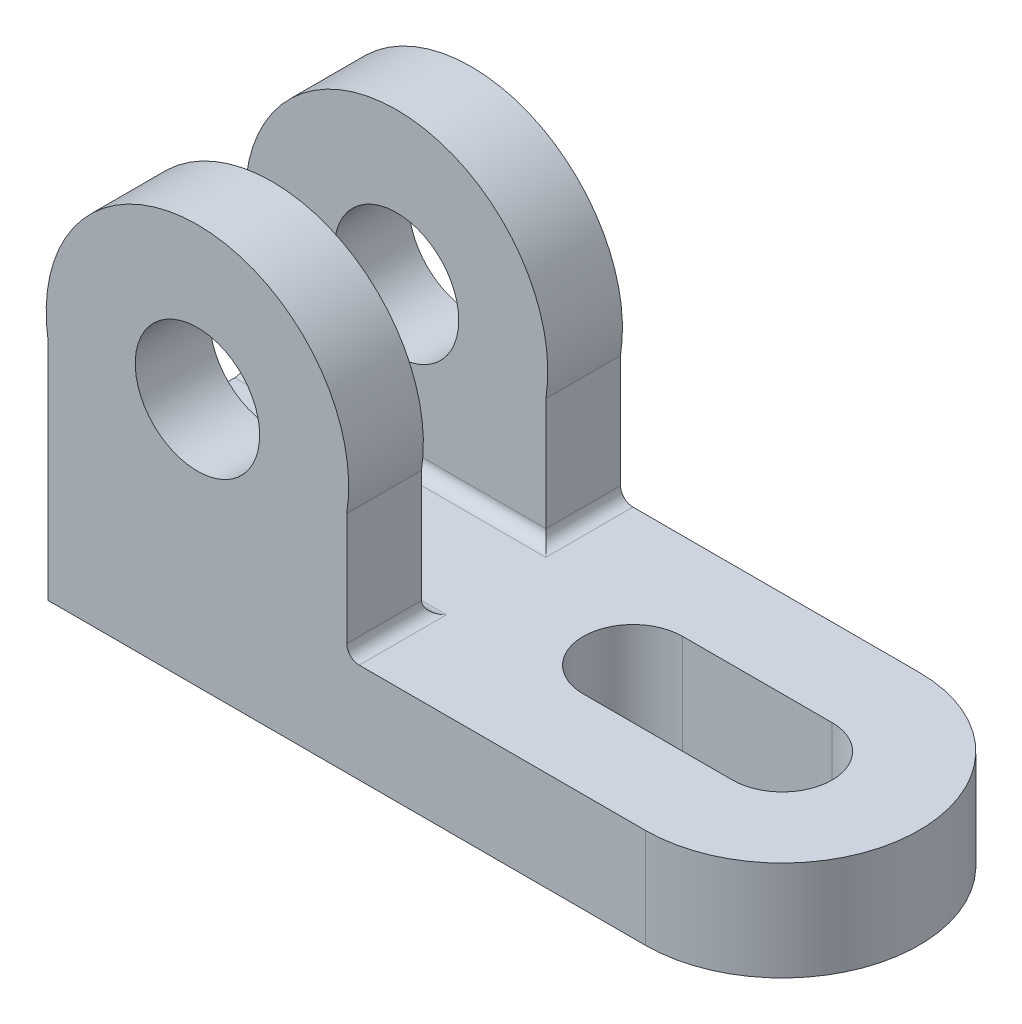
SolidWorks part; units mm, degrees
ref_plane "Front Plane" through (0, 0, 0) normal (0, 0, 1) x (1, 0, 0)
ref_plane "Top Plane" through (0, 0, 0) normal (0, 1, 0) x (1, 0, 0)
ref_plane "Right Plane" through (0, 0, 0) normal (1, 0, 0) x (0, 0, -1)
sketch "Sketch2" plane through (0, 0, 0) normal (0, 1, 0) x (1, 0, 0)
  line L1 (-59, 22) -> (59, 22)
  line L2 (-59, 22) -> (-59, -22)
  line L3 (-59, -22) -> (59, -22)
  line L4 (59, 22) -> (59, -22)
  line L5 (-59, 22) -> (59, -22) construction
  line L6 (-59, -22) -> (59, 22) construction
  circle A0 centre (37, 0) radius 22
  point P0 (0, 0)
  dimension "D1" = 118
  dimension "D2" = 44
extrude "Boss-Extrude1" add sketch "Sketch2" along normal blind 16 contours A0 L1 L2 L3 | A0 L1
sketch "Sketch3" plane through (0, 16, 0) normal (0, 1, 0) x (1, 0, 0)
  line L0 (37, 0) -> (13, 0) construction
  line L1 (37, -8) -> (13, -8)
  line L2 (37, 8) -> (13, 8)
  arc A0 (37, -8) -> (37, 8) centre (37, 0) ccw
  arc A1 (13, 8) -> (13, -8) centre (13, 0) ccw
  point P4 (25, 0)
  dimension "D2" = 8
  dimension "D1" = 24
extrude "Cut-Extrude1" cut sketch "Sketch3" against normal blind 16
ref_plane "Plane1" through (-59, 0, 22) normal (1, 0, 0) x (0, 0, -1)
sketch "Sketch5" plane through (0, 0, 22) normal (0, 0, 1) x (1, 0, 0)
  line L0 (-59, -26.4) -> (-59, 26.4) construction
  line L1 (-59, 16) -> (-11, 16)
  line L2 (-59, 16) -> (-59, 40)
  line L3 (-59, 40) -> (-11, 40)
  line L4 (-11, 16) -> (-11, 40)
  line L5 (-59, 16) -> (37, 16) construction
  line L6 (-59, 0) -> (37, 0) construction
  circle A0 centre (-35, 40) radius 24.3157
  circle A1 centre (-35, 40) radius 10
  line M7 (37, 16) -> (-59, 16)
  dimension "D3" = 20
  dimension "D1" = 40
  dimension "D2" = 48
extrude "Boss-Extrude2" add sketch "Sketch5" against normal blind 12 contours A1 L3 L2 A0 L1 L4 | A0 L2 M7 | A0 L4 M7 | A1 L3 L4 A0 L2
mirror "Mirror1" about plane through (0, 0, 0) normal (0, 0, 1) of "Boss-Extrude2"
fillet "Fillet1" radius 2 4 edges at (-11, 16, 16) (-35, 16, 10) (-11, 16, -16) (-35, 16, -10)
